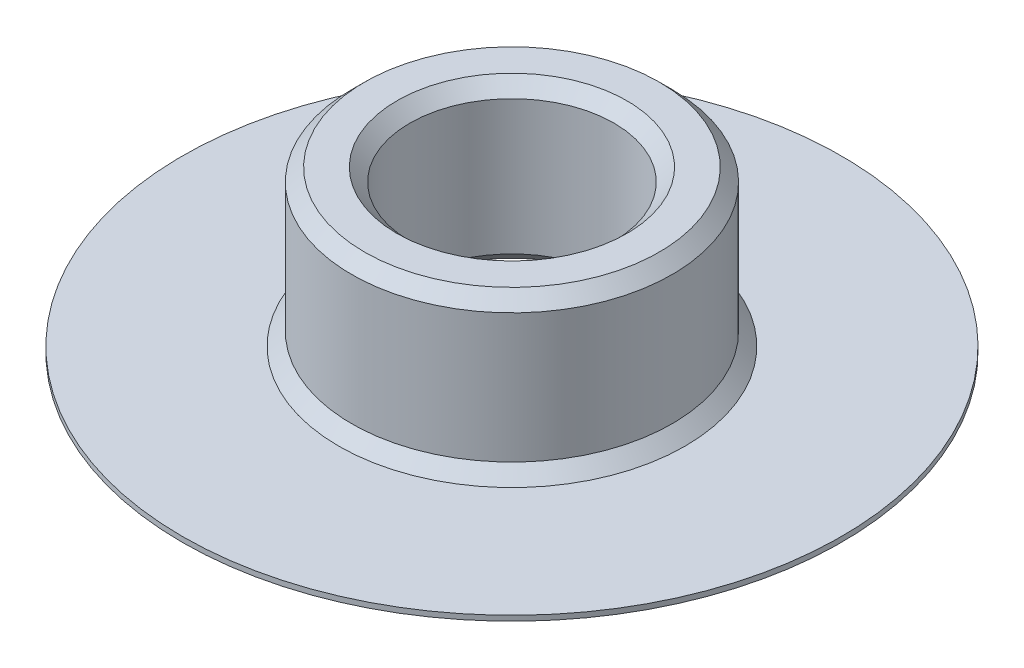
SolidWorks part; units mm, degrees
ref_plane "Спереди" through (0, 0, 0) normal (0, 0, 1) x (1, 0, 0)
ref_plane "Сверху" through (0, 0, 0) normal (0, 1, 0) x (1, 0, 0)
ref_plane "Справа" through (0, 0, 0) normal (1, 0, 0) x (0, 0, -1)
sketch "Эскиз1" plane through (0, 0, 0) normal (0, 1, 0) x (1, 0, 0)
  circle A0 centre (0, 0) radius 12.75
  dimension "D1" = 25.5
extrude "Бобышка-Вытянуть1" add sketch "Эскиз1" along normal blind 0.2
sketch "Эскиз2" plane through (0, 0.2, 0) normal (0, 1, 0) x (1, 0, 0)
  circle A0 centre (0, 0) radius 6.2
  dimension "D1" = 12.4
extrude "Бобышка-Вытянуть2" add sketch "Эскиз2" along normal offset from surface (6 mm away) 6.2 up to face at (0, 0, 12.75)
sketch "Эскиз3" plane through (0, 6.2, 0) normal (0, 1, 0) x (1, 0, 0)
  circle A0 centre (0, 0) radius 3.95
  dimension "D1" = 7.9
extrude "Вырез-Вытянуть1" cut sketch "Эскиз3" against normal through all
chamfer "Фаска1" distance 0.5 angle 45 4 edges at (0, 6.2, 3.95) (0, 6.2, 6.2) (0, 0.2, 6.2) (0, 0, 3.95)
